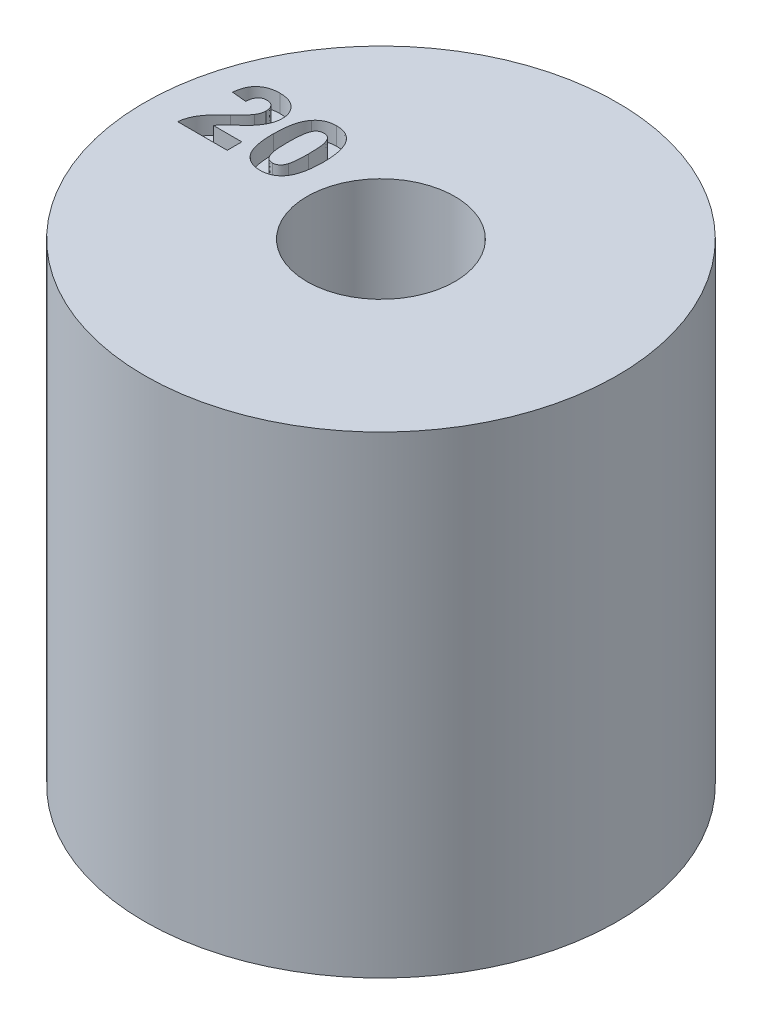
SolidWorks part; units mm, degrees
ref_plane "Front Plane" through (0, 0, 0) normal (0, 0, 1) x (1, 0, 0)
ref_plane "Top Plane" through (0, 0, 0) normal (0, 1, 0) x (1, 0, 0)
ref_plane "Right Plane" through (0, 0, 0) normal (1, 0, 0) x (0, 0, -1)
sketch "Sketch1" plane through (0, 0, 0) normal (0, 1, 0) x (1, 0, 0)
  circle A0 centre (0, 0) radius 8
  circle A1 centre (0, 0) radius 2.5
  dimension "D1" = 16
  dimension "D2" = 5
extrude "Boss-Extrude1" add sketch "Sketch1" along normal blind 16
sketch "Sketch2" plane through (0, 16, 0) normal (0, 1, 0) x (1, 0, 0)
  line L0 (-8, 0) -> (8, 0) construction
  circle A0 centre (0, 0) radius 8 construction
  text T0 " 20" font "Arial" height in points 10
extrude "Cut-Extrude1" cut sketch "Sketch2" against normal blind 0.6
